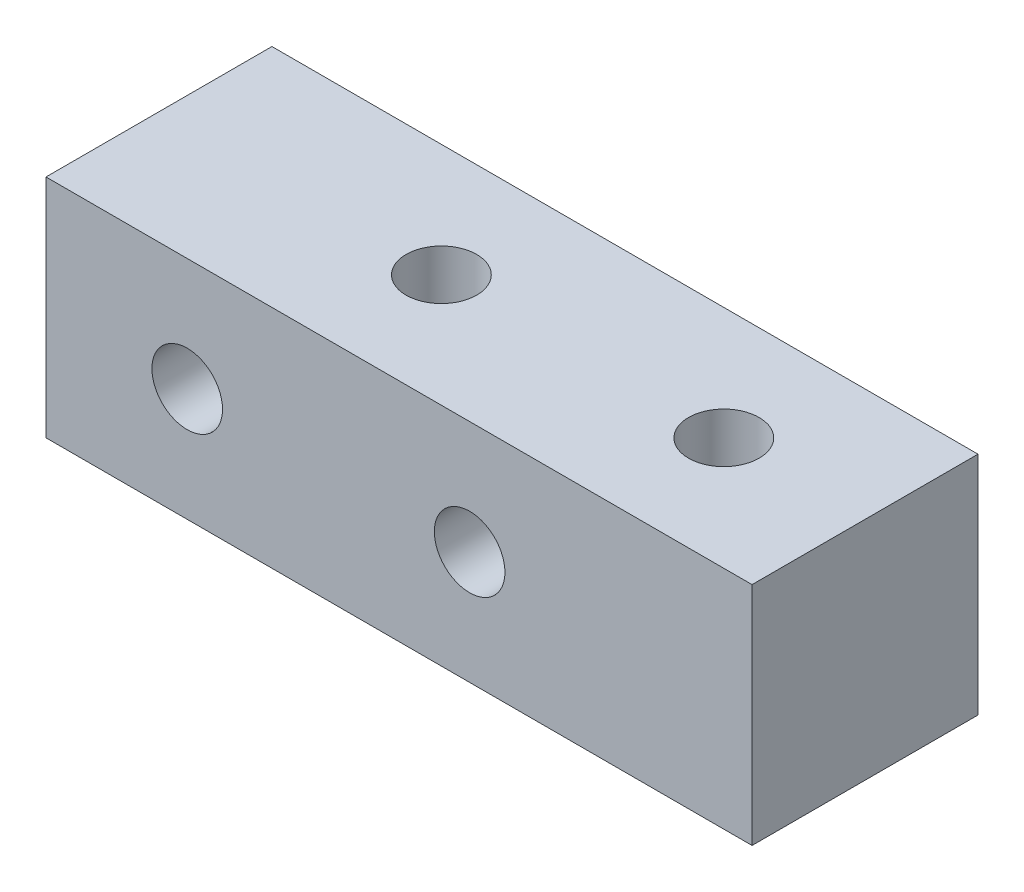
SolidWorks part; units mm, degrees
material "6061 合金"
ref_plane "前视基准面" through (0, 0, 0) normal (0, 0, 1) x (1, 0, 0)
ref_plane "上视基准面" through (0, 0, 0) normal (0, 1, 0) x (1, 0, 0)
ref_plane "右视基准面" through (0, 0, 0) normal (1, 0, 0) x (0, 0, -1)
sketch "草图1" plane through (0, 0, 0) normal (0, 0, 1) x (1, 0, 0)
  line L1 (12.5, -4) -> (-12.5, -4)
  line L2 (12.5, -4) -> (12.5, 4)
  line L3 (12.5, 4) -> (-12.5, 4)
  line L4 (-12.5, -4) -> (-12.5, 4)
  line L5 (12.5, -4) -> (-12.5, 4) construction
  line L6 (12.5, 4) -> (-12.5, -4) construction
  point P0 (0, 0)
  dimension "D1" = 25
  dimension "D2" = 8
extrude "凸台-拉伸1" add sketch "草图1" along normal blind 8
sketch "草图2" plane through (0, 0, 8) normal (0, 0, 1) x (1, 0, 0)
  line L0 (-12.5, 4) -> (-12.5, -4) construction
  point P0 (-7.5, 0)
  point P1 (2.5, 0)
  dimension "D1" = 5
  dimension "D2" = 10
sketch "草图3" plane through (0, 0, 8) normal (0, 0, 1) x (1, 0, 0)
sketch "草图4" plane through (0, 4, 0) normal (0, 1, 0) x (1, 0, 0)
  line L0 (12.5, -8) -> (12.5, 0) construction
  point P0 (7.5, -4)
  point P1 (-2.5, -4)
  dimension "D1" = 5
  dimension "D2" = 10
hole_wizard "M3 螺纹孔的螺纹孔钻头1" positions "3D草图1" profile "草图5" hole size "M3" standard "DIN" end condition through all
sketch3d "3D草图1"
  point P0 (-2.5, 4, 4)
  point P3 (7.5, 4, 4)
  point P6 (2.5, 0, 8)
  point P9 (-7.5, 0, 8)
sketch "草图5" plane through (-2.5, 4, 4) normal (1, 0, 0) x (0, 0, 1)
  line L0 (0, 0) -> (0, 8)
  line L1 (0, 8) -> (1.25, 8)
  line L2 (1.25, 8) -> (1.25, 0)
  line L5 (1.25, 0) -> (0, 0)
  line L11 (0, -6.35) -> (0, 107.95) construction
  dimension "通孔孔直径" = 2.5
  dimension "通孔孔深度" = 8
